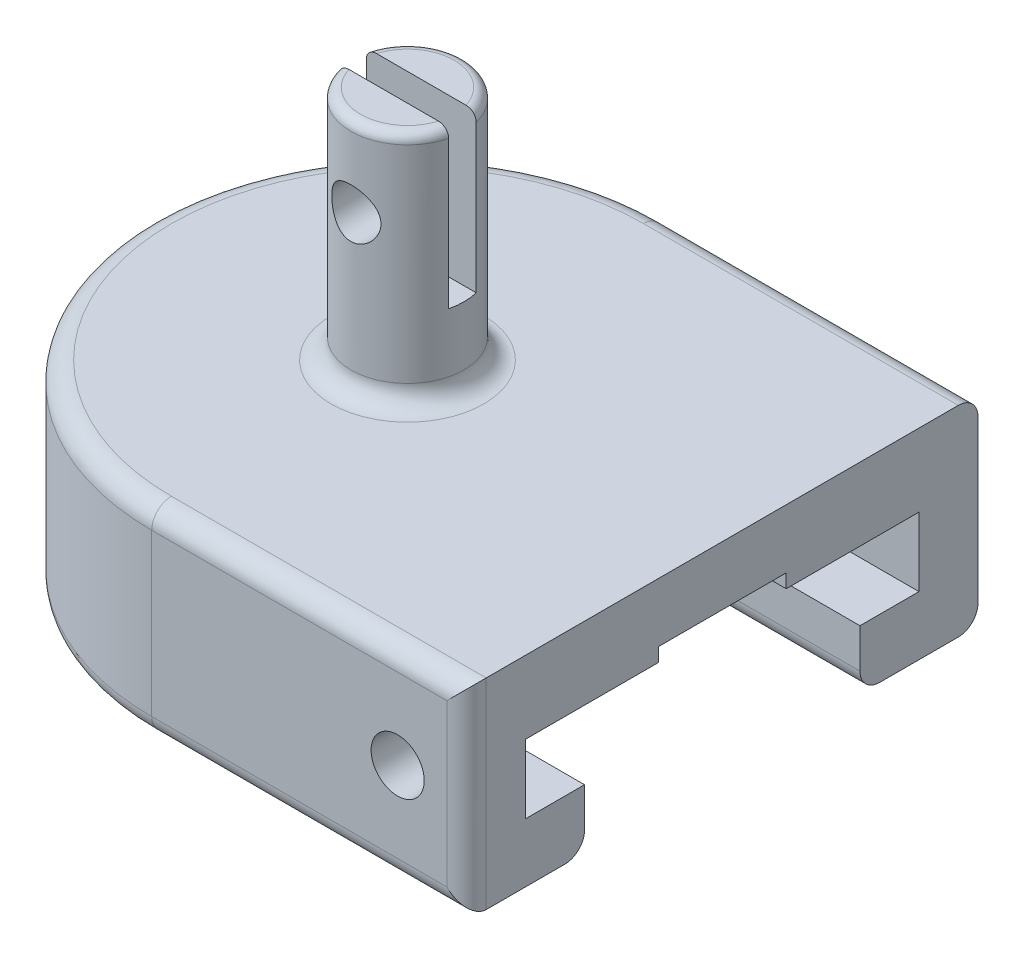
SolidWorks part; units mm, degrees
ref_plane "Front Plane" through (0, 0, 0) normal (0, 0, 1) x (1, 0, 0)
ref_plane "Top Plane" through (0, 0, 0) normal (0, 1, 0) x (1, 0, 0)
ref_plane "Right Plane" through (0, 0, 0) normal (1, 0, 0) x (0, 0, -1)
sketch "Sketch1" plane through (0, 0, 0) normal (0, 1, 0) x (1, 0, 0)
  line L0 (0, 13) -> (16, 13)
  line L1 (0, -13) -> (16, -13)
  line L2 (0, 7) -> (16, 7)
  line L3 (16, 13) -> (16, 7)
  line L4 (0, -7) -> (16, -7)
  line L5 (16, -7) -> (16, -13)
  arc A0 (0, 7) -> (0, -7) centre (0, 0) ccw
  arc A1 (0, 13) -> (0, -13) centre (0, 0) ccw
  dimension "D1" = 6
  dimension "D2" = 7
  dimension "D3" = 16
  dimension "D4" = 16
extrude "Boss-Extrude1" add sketch "Sketch1" along normal blind 3
sketch "Sketch2" plane through (0, 3, 0) normal (0, 1, 0) x (1, 0, 0)
  line L0 (0, 13) -> (16, 13)
  line L1 (16, 13) -> (16, 10)
  line L2 (16, 7) -> (16, 13) construction
  line L3 (16, -13) -> (0, -13)
  line L4 (16, -13) -> (16, -10)
  line L7 (16, -13) -> (16, -7) construction
  line L8 (0, 10) -> (16, 10)
  line L9 (0, -10) -> (16, -10)
  arc A0 (0, 10) -> (0, -10) centre (0, 0) ccw
  arc A1 (0, 13) -> (0, -13) centre (0, 0) ccw
  dimension "D2" = 3
extrude "Boss-Extrude2" add sketch "Sketch2" along normal blind 3.5
sketch "Sketch3" plane through (0, 6.5, 0) normal (0, 1, 0) x (1, 0, 0)
  line L0 (16, 13) -> (0, 13)
  line L1 (16, 13) -> (16, 7)
  line L3 (0, -13) -> (16, -13)
  line L4 (16, -13) -> (16, -7)
  line L5 (16, -7) -> (0, -7) construction
  line L6 (16, -10) -> (16, -7) construction
  line L8 (16, 7) -> (16, -7)
  arc A1 (0, 13) -> (0, -13) centre (0, 0) ccw
extrude "Boss-Extrude3" add sketch "Sketch3" along normal blind 3.7
sketch "Sketch4" plane through (0, 10.2, 0) normal (0, 1, 0) x (1, 0, 0)
  circle A0 centre (0, 0) radius 2.88
  dimension "D1" = 5.76
extrude "Boss-Extrude4" add sketch "Sketch4" along normal blind 12
sketch "Sketch11" plane through (16, 0, 0) normal (1, 0, 0) x (0, 0, -1)
  line L5 (-10, 6.5) -> (10, 6.5) construction
  line L6 (-3.25, 6.5) -> (3.25, 6.5)
  line L7 (-3.25, 6.5) -> (-3.25, 7.2)
  line L8 (-3.25, 7.2) -> (3.25, 7.2)
  line L9 (3.25, 6.5) -> (3.25, 7.2)
  line L10 (0, 10.2) -> (0, 6.5) construction
  line L11 (-13, 10.2) -> (13, 10.2) construction
  line L12 (0, 7.2) -> (0, 6.5) construction
  dimension "D1" = 0.7
  dimension "D2" = 6.5
extrude "Cut-Extrude3" cut sketch "Sketch11" against normal blind 23
hole_wizard "Ø2.5mm Dowel Hole1" positions "3DSketch4" profile "Sketch7" hole size "Ø2.5" standard "ANSI Metric" end condition through all
sketch3d "3DSketch4"
  point P0 (-0.0024, 18.1049, 2.88)
  point P12 (-0.0024, 18.1049, 2.88)
sketch "Sketch7" plane through (-0.0024, 18.1049, 2.88) normal (0, 1, 0) x (1, 0, 0.0008)
  line L0 (0, 0) -> (0, 15.8935)
  line L1 (0, 15.8935) -> (1.25, 15.8935)
  line L2 (1.25, 15.8935) -> (1.25, 0)
  line L5 (1.25, 0) -> (0, 0)
  line L11 (0, -6.35) -> (0, 107.95) construction
  dimension "Thru Hole Dia." = 2.5
  dimension "Thru Hole Depth" = 15.8935
sketch "Sketch8" plane through (0, 0, 13) normal (0, 0, 1) x (1, 0, 0)
  line L0 (16, 5.1) -> (0, 5.1) construction
  line L1 (16, 10.2) -> (16, 0) construction
  line L2 (0, 10.2) -> (0, 0) construction
  circle A0 centre (12.5, 5.1) radius 1.35
  dimension "D1" = 2.7
  dimension "D2" = 3.5
extrude "Cut-Extrude1" cut sketch "Sketch8" against normal through all
fillet "Fillet1" radius 1 10 edges at (8, 10.2, -13) (-13, 10.2, 0) (8, 0, -13) (-13, 0, 0) (8, 10.2, 13) (16, 5.1, 13) (8, 0, 13) (8, 0, -7) (-7, 0, 0) (8, 0, 7)
fillet "Fillet2" radius 1 1 edges at (0, 10.2, 2.88)
sketch "Sketch10" plane through (0, 22.2, 0) normal (0, 1, 0) x (1, 0, 0)
  line L0 (-2.7936, 0.7) -> (2.7936, 0.7)
  line L1 (-2.7936, -0.7) -> (2.7936, -0.7)
  line L2 (-2.88, 0) -> (2.88, 0) construction
  circle A0 centre (0, 0) radius 2.88 construction
  circle A1 centre (0, 0) radius 2.88 construction
  arc A2 (2.7936, -0.7) -> (2.7936, 0.7) centre (0, 0) ccw
  arc A3 (-2.7936, 0.7) -> (-2.7936, -0.7) centre (0, 0) ccw
  dimension "D2" = 0.7
  dimension "D3" = 0.7
extrude "Cut-Extrude2" cut sketch "Sketch10" against normal blind 8
fillet "Fillet3" radius 0.5 2 edges at (0, 22.2, -2.88) (0, 22.2, 2.88)
